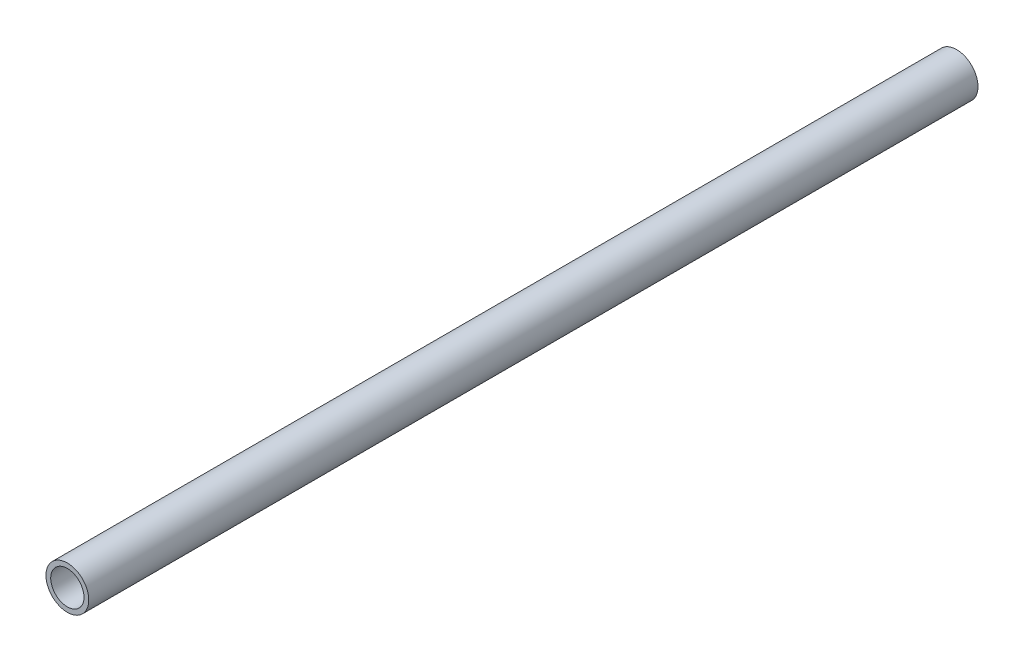
SolidWorks part; units mm, degrees
ref_plane "前视基准面" through (0, 0, 0) normal (0, 0, 1) x (1, 0, 0)
ref_plane "上视基准面" through (0, 0, 0) normal (0, 1, 0) x (1, 0, 0)
ref_plane "右视基准面" through (0, 0, 0) normal (1, 0, 0) x (0, 0, -1)
other "Configuration Table"
sketch "草图1" plane through (0, 0, 0) normal (0, 0, 1) x (1, 0, 0)
  circle A0 centre (0, 0) radius 7
  circle A1 centre (0, 0) radius 9
  dimension "D1" = 14
  dimension "D2" = 18
extrude "凸台-拉伸1" add sketch "草图1" along normal blind 373.98
